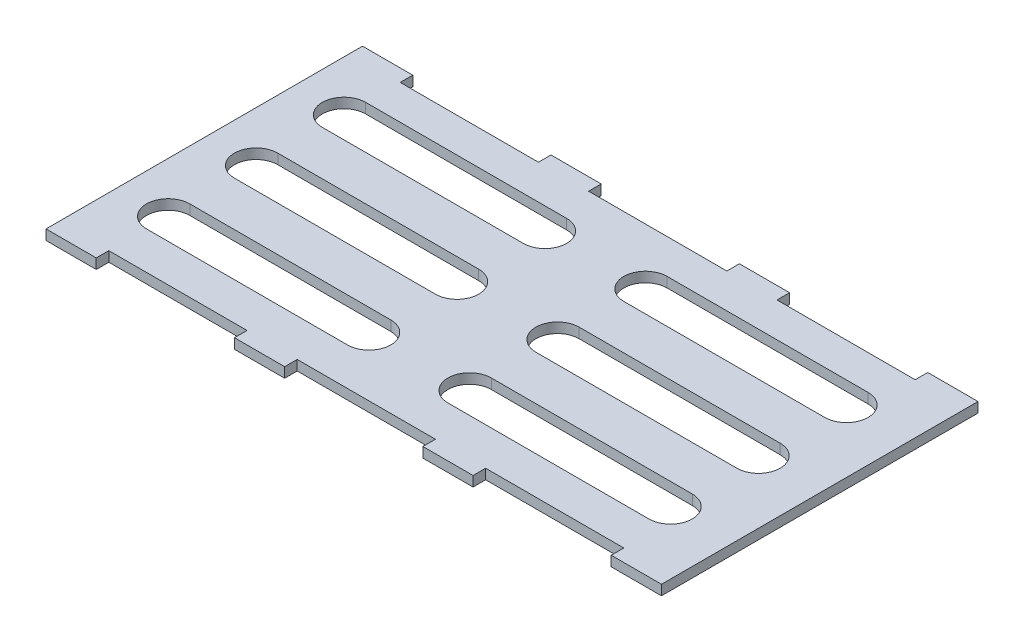
SolidWorks part; units mm, degrees
ref_plane "Front Plane" through (0, 0, 0) normal (0, 0, 1) x (1, 0, 0)
ref_plane "Top Plane" through (0, 0, 0) normal (0, 1, 0) x (1, 0, 0)
ref_plane "Right Plane" through (0, 0, 0) normal (1, 0, 0) x (0, 0, -1)
sketch "Sketch1" plane through (0, 0, 0) normal (0, 1, 0) x (1, 0, 0)
  line L0 (-69.5349, 105.2587) -> (-49.5349, 105.2587)
  line L1 (-124.5349, 100.2587) -> (-69.4964, 100.2587)
  line L2 (-144.5349, 105.2587) -> (-144.5349, -20.7413)
  line L3 (-124.5349, -15.7413) -> (-69.4964, -15.7413)
  line L4 (100.4651, 100.2587) -> (100.4651, -15.7413)
  line L7 (-144.5349, 105.2587) -> (-124.5349, 105.2587)
  line L8 (-124.5349, 100.2587) -> (-124.5349, 105.2587)
  line L9 (-49.5349, 100.2587) -> (-49.5349, 105.2587)
  line L10 (-69.4964, 100.2587) -> (-69.5349, 105.2587)
  line L11 (5.4651, 105.2587) -> (25.4651, 105.2587)
  line L12 (25.4651, 100.2587) -> (25.4651, 105.2587)
  line L13 (5.5036, 100.2587) -> (5.4651, 105.2587)
  line L14 (80.4651, 105.2587) -> (100.4651, 105.2587)
  line L15 (100.4651, 100.2587) -> (100.4651, 105.2587)
  line L16 (80.4651, 100.2587) -> (80.4651, 105.2587)
  line L17 (-49.5349, 100.2587) -> (5.5036, 100.2587)
  line L18 (25.4651, 100.2587) -> (80.4651, 100.2587)
  line L19 (-4.5349, 86.5143) -> (75.4651, 86.5143)
  line L20 (25.4651, -15.7413) -> (80.4651, -15.7413)
  line L21 (-49.5349, -15.7413) -> (5.5036, -15.7413)
  line L22 (80.4651, -15.7413) -> (80.4651, -20.7413)
  line L23 (100.4651, -15.7413) -> (100.4651, -20.7413)
  line L24 (80.4651, -20.7413) -> (100.4651, -20.7413)
  line L25 (5.5036, -15.7413) -> (5.4651, -20.7413)
  line L26 (25.4651, -15.7413) -> (25.4651, -20.7413)
  line L27 (5.4651, -20.7413) -> (25.4651, -20.7413)
  line L28 (-69.4964, -15.7413) -> (-69.5349, -20.7413)
  line L29 (-49.5349, -15.7413) -> (-49.5349, -20.7413)
  line L30 (-124.5349, -15.7413) -> (-124.5349, -20.7413)
  line L31 (-144.5349, -20.7413) -> (-124.5349, -20.7413)
  line L32 (-124.5349, -15.7413) -> (-69.4964, -15.7413)
  line L33 (-69.5349, -20.7413) -> (-49.5349, -20.7413)
  line L34 (-49.5349, -15.7413) -> (5.5036, -15.7413)
  line L35 (25.4651, -15.7413) -> (80.4651, -15.7413)
  line L36 (-4.5349, 69.2611) -> (75.4651, 69.2611)
  line L37 (-124.5349, 86.5143) -> (-44.5349, 86.5143)
  line L39 (-124.5349, 69.2611) -> (-44.5349, 69.2611)
  line L41 (-4.5349, 51.5143) -> (75.4651, 51.5143)
  line L42 (-4.5349, 34.2611) -> (75.4651, 34.2611)
  line L43 (-4.5349, 16.5143) -> (75.4651, 16.5143)
  line L44 (-4.5349, -0.7389) -> (75.4651, -0.7389)
  line L45 (-124.5349, 51.5143) -> (-44.5349, 51.5143)
  line L46 (-124.5349, 34.2611) -> (-44.5349, 34.2611)
  line L47 (-124.5349, 16.5143) -> (-44.5349, 16.5143)
  line L48 (-124.5349, -0.7389) -> (-44.5349, -0.7389)
  arc A0 (-124.5349, 86.5143) -> (-124.5349, 69.2611) centre (-124.5349, 77.8877) ccw
  arc A1 (-44.5349, 86.5143) -> (-44.5349, 69.2611) centre (-44.5349, 77.8877) cw
  arc A2 (-4.5349, 86.5143) -> (-4.5349, 69.2611) centre (-4.5349, 77.8877) ccw
  arc A3 (75.4651, 86.5143) -> (75.4651, 69.2611) centre (75.4651, 77.8877) cw
  arc A4 (-4.5349, 51.5143) -> (-4.5349, 34.2611) centre (-4.5349, 42.8877) ccw
  arc A5 (75.4651, 51.5143) -> (75.4651, 34.2611) centre (75.4651, 42.8877) cw
  arc A6 (-4.5349, 16.5143) -> (-4.5349, -0.7389) centre (-4.5349, 7.8877) ccw
  arc A7 (75.4651, 16.5143) -> (75.4651, -0.7389) centre (75.4651, 7.8877) cw
  arc A8 (-124.5349, 51.5143) -> (-124.5349, 34.2611) centre (-124.5349, 42.8877) ccw
  arc A9 (-44.5349, 51.5143) -> (-44.5349, 34.2611) centre (-44.5349, 42.8877) cw
  arc A10 (-124.5349, 16.5143) -> (-124.5349, -0.7389) centre (-124.5349, 7.8877) ccw
  arc A11 (-44.5349, 16.5143) -> (-44.5349, -0.7389) centre (-44.5349, 7.8877) cw
  dimension "D1" = 245
  dimension "D2" = 116
  dimension "D3" = 20
  dimension "D4" = 5
  dimension "D6" = 80
  dimension "D5" = 4
  dimension "D7" = 2
  dimension "D8" = 3
extrude "Boss-Extrude1" add sketch "Sketch1" along normal blind 4 contours L28 L33 L29 L21 L25 L27 L26 L20 L22 L24 L23 L4 L15 L14 L16 L18 L12 L11 L13 L17 L9 L0 L10 L1 L8 L7 L2 L31 L30 L3 L37 A1 L39 A0 L19 A3 L36 A2 L41 A5 L42 A4 L43 A7 L44 A6
